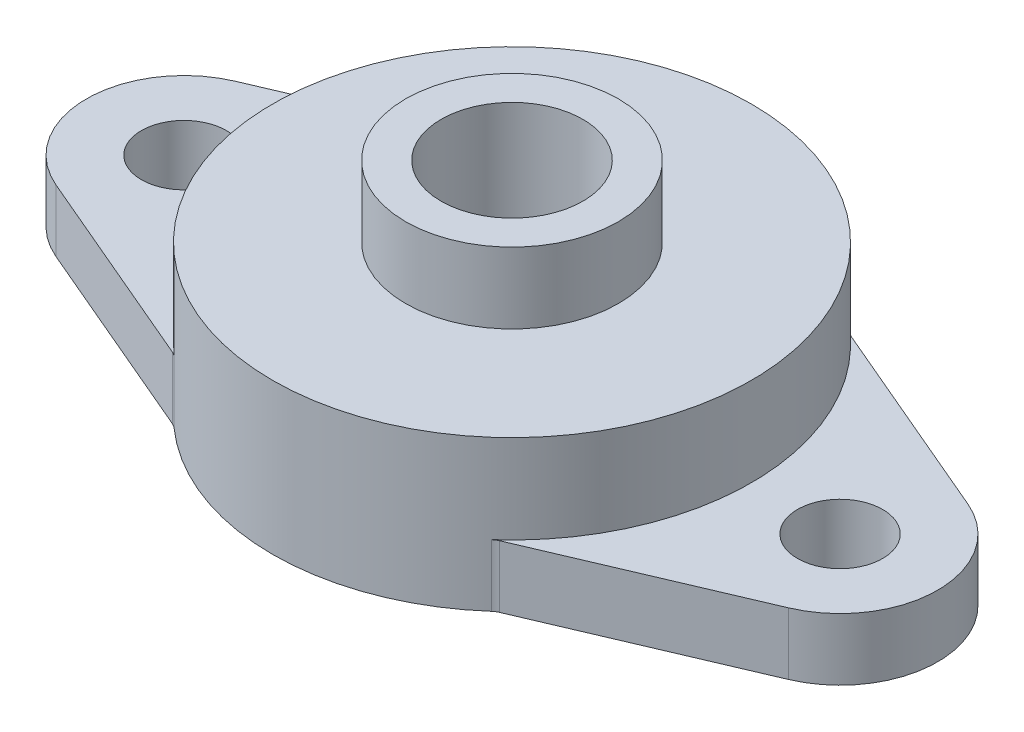
SolidWorks part; units mm, degrees
ref_plane "Front Plane" through (0, 0, 0) normal (0, 0, 1) x (1, 0, 0)
ref_plane "Top Plane" through (0, 0, 0) normal (0, 1, 0) x (1, 0, 0)
ref_plane "Right Plane" through (0, 0, 0) normal (1, 0, 0) x (0, 0, -1)
sketch "Sketch1" plane through (0, 0, 0) normal (0, 1, 0) x (1, 0, 0)
  line L0 (-18.5, 0) -> (18.5, 0) construction
  line L1 (-20.6571, 5.0593) -> (-9.2212, 9.9352)
  line L2 (-20.6571, -5.0593) -> (-9.2212, -9.9352)
  line L3 (20.6571, 5.0593) -> (9.2212, 9.9352)
  line L5 (20.6571, -5.0593) -> (9.2212, -9.9352)
  arc A0 (-8.9504, -10.1064) -> (8.9504, -10.1064) centre (0, 0) ccw
  arc A1 (-20.6571, 5.0593) -> (-20.6571, -5.0593) centre (-18.5, 0) ccw
  arc A2 (20.6571, -5.0593) -> (20.6571, 5.0593) centre (18.5, 0) ccw
  arc A3 (8.9504, 10.1064) -> (-8.9504, 10.1064) centre (0, 0) ccw
  arc A4 (9.2212, -9.9352) -> (8.9504, -10.1064) centre (9.6134, -10.8551) ccw
  arc A5 (9.2212, 9.9352) -> (8.9504, 10.1064) centre (9.6134, 10.8551) cw
  arc A6 (-9.2212, -9.9352) -> (-8.9504, -10.1064) centre (-9.6134, -10.8551) cw
  arc A7 (-9.2212, 9.9352) -> (-8.9504, 10.1064) centre (-9.6134, 10.8551) ccw
  point P6 (0, 0)
  point P17 (9.0692, 10)
  point P20 (-9.0692, -10)
  point P23 (-9.0692, 10)
  dimension "D2" = 27
  dimension "D3" = 11
  dimension "D5" = 1
  dimension "D1" = 37
  dimension "D4" = 20
extrude "Boss-Extrude1" add sketch "Sketch1" along normal blind 3.5
sketch "Sketch2" plane through (0, 3.5, 0) normal (0, 1, 0) x (1, 0, 0)
  circle A0 centre (0, 0) radius 13.5
  arc A1 (8.9504, 10.1064) -> (-8.9504, 10.1064) centre (0, 0) ccw construction
extrude "Boss-Extrude2" add sketch "Sketch2" along normal blind 5
sketch "Sketch3" plane through (0, 8.5, 0) normal (0, 1, 0) x (1, 0, 0)
  circle A0 centre (0, 0) radius 6
  dimension "D1" = 12
extrude "Boss-Extrude3" add sketch "Sketch3" along normal blind 4
sketch "Sketch4" plane through (0, 12.5, 0) normal (0, 1, 0) x (1, 0, 0)
  circle A0 centre (0, 0) radius 4
  dimension "D1" = 8
extrude "Cut-Extrude1" cut sketch "Sketch4" against normal through all
sketch "Sketch5" plane through (0, 3.5, 0) normal (0, 1, 0) x (1, 0, 0)
  circle A0 centre (-18.5, 0) radius 2.4
  circle A1 centre (18.5, 0) radius 2.4
  dimension "D1" = 4.8
extrude "Cut-Extrude2" cut sketch "Sketch5" against normal through all
